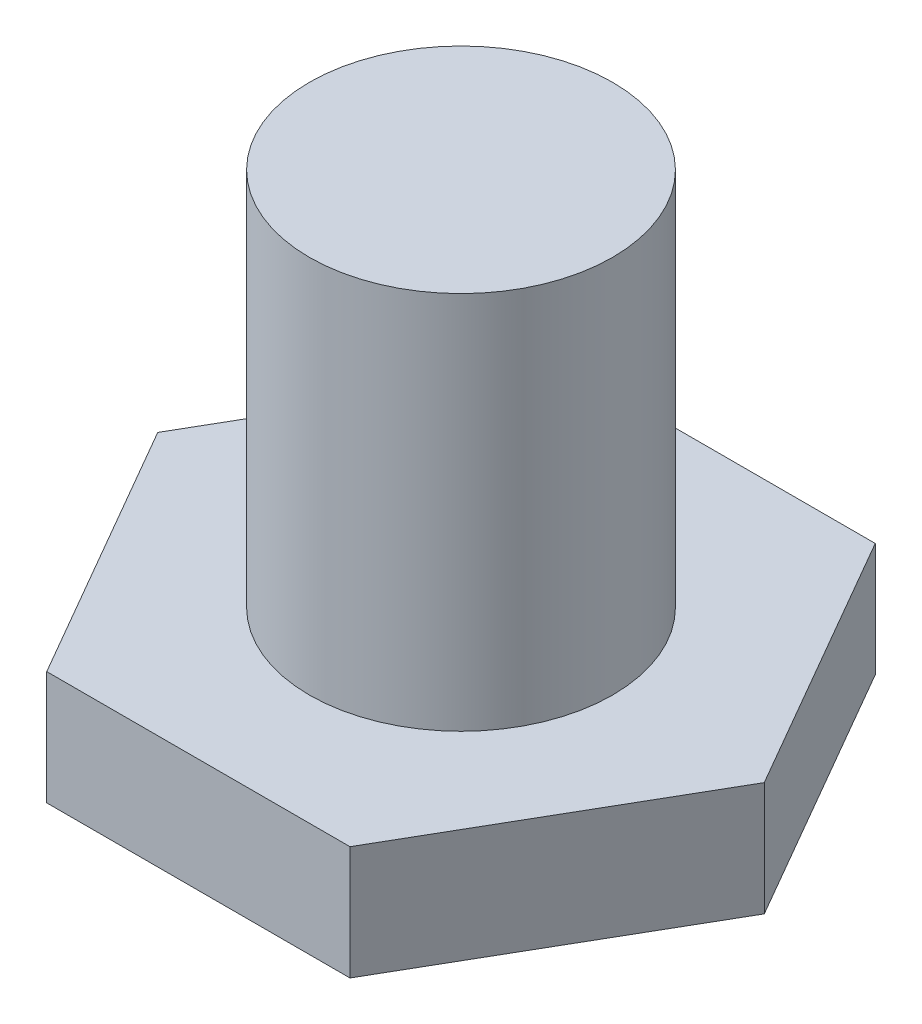
SolidWorks part; units mm, degrees
ref_plane "前视基准面" through (0, 0, 0) normal (0, 0, 1) x (1, 0, 0)
ref_plane "上视基准面" through (0, 0, 0) normal (0, 1, 0) x (1, 0, 0)
ref_plane "右视基准面" through (0, 0, 0) normal (1, 0, 0) x (0, 0, -1)
other "Configuration Table"
sketch "草图1" plane through (0, 0, 0) normal (0, 1, 0) x (1, 0, 0)
  line L1 (4, 0) -> (2, 3.4641)
  line L2 (2, 3.4641) -> (-2, 3.4641)
  line L3 (-2, 3.4641) -> (-4, 0)
  line L4 (-4, 0) -> (-2, -3.4641)
  line L5 (-2, -3.4641) -> (2, -3.4641)
  line L6 (2, -3.4641) -> (4, 0)
  circle A0 centre (0, 0) radius 3.4641 construction
  dimension "D1" = 4
extrude "凸台-拉伸1" add sketch "草图1" along normal blind 1.5
sketch "草图2" plane through (0, 1.5, 0) normal (0, 1, 0) x (1, 0, 0)
  circle A0 centre (0, 0) radius 2
  dimension "D1" = 4
extrude "凸台-拉伸2" add sketch "草图2" along normal blind 5
